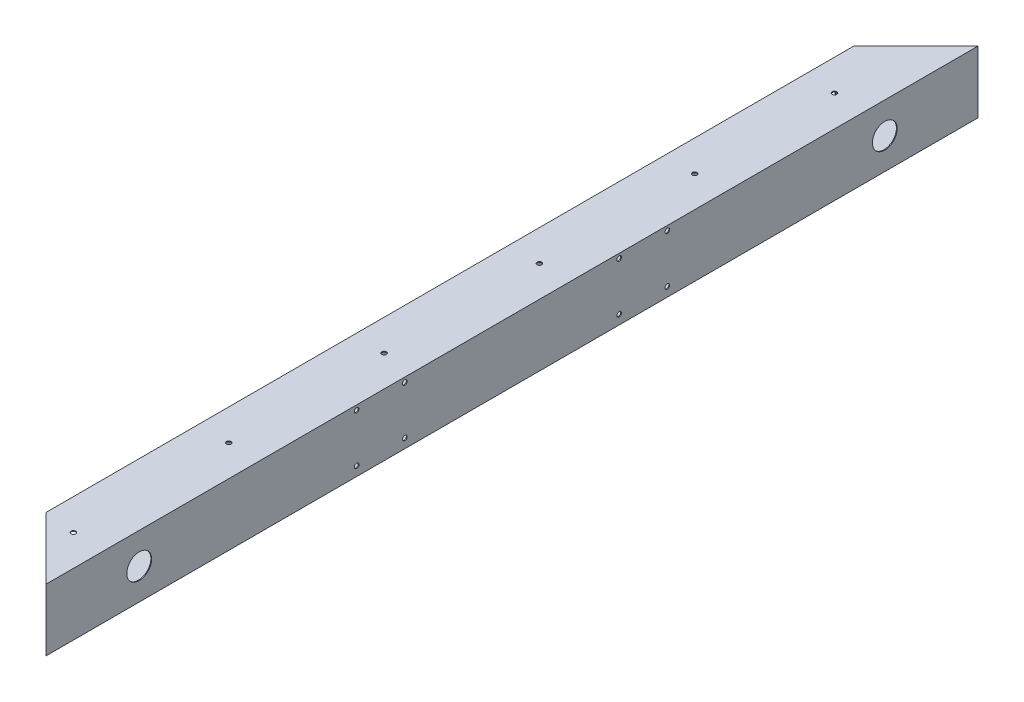
SolidWorks part; units mm, degrees
ref_plane "Alzado" through (0, 0, 0) normal (0, 0, 1) x (1, 0, 0)
ref_plane "Planta" through (0, 0, 0) normal (0, 1, 0) x (1, 0, 0)
ref_plane "Vista lateral" through (0, 0, 0) normal (1, 0, 0) x (0, 0, -1)
sketch "Croquis1" plane through (0, 0, 0) normal (0, 0, 1) x (1, 0, 0)
  line L1 (-20, 20) -> (20, 20)
  line L2 (-20, 20) -> (-20, -20)
  line L3 (-20, -20) -> (20, -20)
  line L4 (20, 20) -> (20, -20)
  line L5 (-20, 20) -> (20, -20) construction
  line L6 (-20, -20) -> (20, 20) construction
  line L7 (-19.5, 19.5) -> (19.5, 19.5)
  line L8 (-19.5, 19.5) -> (-19.5, -19.5)
  line L9 (-19.5, -19.5) -> (19.5, -19.5)
  line L10 (19.5, 19.5) -> (19.5, -19.5)
  line L11 (-19.5, 19.5) -> (19.5, -19.5) construction
  line L12 (-19.5, -19.5) -> (19.5, 19.5) construction
  point P0 (0, 0)
  point P6 (0, 0)
  dimension "D1" = 40
  dimension "D2" = 40
  dimension "D3" = 39
extrude "Saliente-Extruir2" add sketch "Croquis1" along normal blind 600
sketch "Croquis6" plane through (0, 20, 0) normal (0, 1, 0) x (1, 0, 0)
  line L0 (20, -600) -> (-20, -560)
  line L1 (-20, -600) -> (-20, 0) construction
  line L2 (-20, -560) -> (-20, -600)
  line L3 (-20, -600) -> (20, -600)
  dimension "D1" = 45
extrude "Cortar-Extruir2" cut sketch "Croquis6" against normal blind 600
sketch "Croquis5" plane through (0, 20, 0) normal (0, 1, 0) x (1, 0, 0)
  line L0 (20, 0) -> (-20, -40)
  line L1 (-20, -560) -> (-20, 0) construction
  line L2 (20, 0) -> (-20, 0) construction
  line L3 (-20, -40) -> (-20, 0)
  line L4 (-20, 0) -> (20, 0)
  dimension "D1" = 45
extrude "Cortar-Extruir1" cut sketch "Croquis5" against normal blind 600
sketch "Croquis7" plane through (20, 0, 0) normal (1, 0, 0) x (0, 0, -1)
  line L0 (-600, 0) -> (-540, 0) construction
  line L1 (-600, -20) -> (-600, 20) construction
  circle A0 centre (-540, 0) radius 8
  dimension "D2" = 16
  dimension "D1" = 60
extrude "Cortar-Extruir3" cut sketch "Croquis7" against normal blind 550
sketch "Croquis8" plane through (20, 0, 0) normal (1, 0, 0) x (0, 0, -1)
  line L0 (0, 0) -> (-60, 0) construction
  circle A0 centre (-60, 0) radius 8
  dimension "D2" = 16
  dimension "D1" = 60
extrude "Cortar-Extruir4" cut sketch "Croquis8" against normal blind 550
sketch "Croquis9" plane through (0, 20, 0) normal (0, 1, 0) x (1, 0, 0)
  line L0 (0, -662.3804) -> (0, -562.3804) construction
  line L1 (0, -562.3804) -> (0, -462.3804) construction
  line L2 (0, -462.3804) -> (0, -362.3804) construction
  line L3 (0, -362.3804) -> (0, -262.3804) construction
  line L4 (0, -262.3804) -> (0, -162.3804) construction
  line L5 (0, -162.3804) -> (0, -72.3804) construction
  circle A0 centre (0, -562.3804) radius 1.5
  circle A1 centre (0, -462.3804) radius 1.5
  circle A2 centre (0, -362.3804) radius 1.5
  circle A3 centre (0, -262.3804) radius 1.5
  circle A4 centre (0, -162.3804) radius 1.5
  circle A5 centre (0, -72.3804) radius 1.5
  dimension "D2" = 3
  dimension "D4" = 3
  dimension "D6" = 3
  dimension "D8" = 3
  dimension "D10" = 3
  dimension "D12" = 3
  dimension "D1" = 100
  dimension "D3" = 100
  dimension "D5" = 100
  dimension "D7" = 100
  dimension "D9" = 100
  dimension "D11" = 90
extrude "Cortar-Extruir5" cut sketch "Croquis9" against normal blind 550
sketch "Croquis10" plane through (20, 0, 0) normal (1, 0, 0) x (0, 0, -1)
  line L0 (-60, 0) -> (-115, 0) construction
  line L1 (-95.2035, 22) -> (-95.2035, -20) construction
  line L3 (-600, -20) -> (0, -20) construction
  line L4 (-200, 22) -> (-200, 17) construction
  line L5 (-200, 17) -> (-231, 17) construction
  line L6 (-200, 17) -> (-200, -14) construction
  line L7 (-540, 0) -> (-485, 0) construction
  line L8 (-365.3715, 22) -> (-365.3715, -20) construction
  line L9 (-369, 22) -> (-369, 17) construction
  line L10 (-369, 17) -> (-400, 17) construction
  line L11 (-369, 17) -> (-369, -14) construction
  circle A1 centre (-200, 17) radius 1.5
  circle A2 centre (-231, 17) radius 1.5
  circle A3 centre (-200, -14) radius 1.5
  circle A4 centre (-231, -14) radius 1.5
  circle A6 centre (-369, 17) radius 1.5
  circle A7 centre (-400, 17) radius 1.5
  circle A8 centre (-369, -14) radius 1.5
  circle A9 centre (-400, -14) radius 1.5
  dimension "D3" = 3
  dimension "D4" = 3
  dimension "D7" = 3
  dimension "D8" = 3
  dimension "D12" = 3
  dimension "D13" = 3
  dimension "D16" = 3
  dimension "D17" = 3
  dimension "D1" = 42
  dimension "D2" = 5
  dimension "D5" = 31
  dimension "D6" = 31
  dimension "D9" = 55
  dimension "D10" = 42
  dimension "D11" = 5
  dimension "D14" = 31
  dimension "D15" = 31
  dimension "D18" = 55
  dimension "D19" = 140
  dimension "D20" = 6
  dimension "D21" = 6
  dimension "D22" = 140
extrude "Cortar-Extruir6" cut sketch "Croquis10" against normal blind 550
